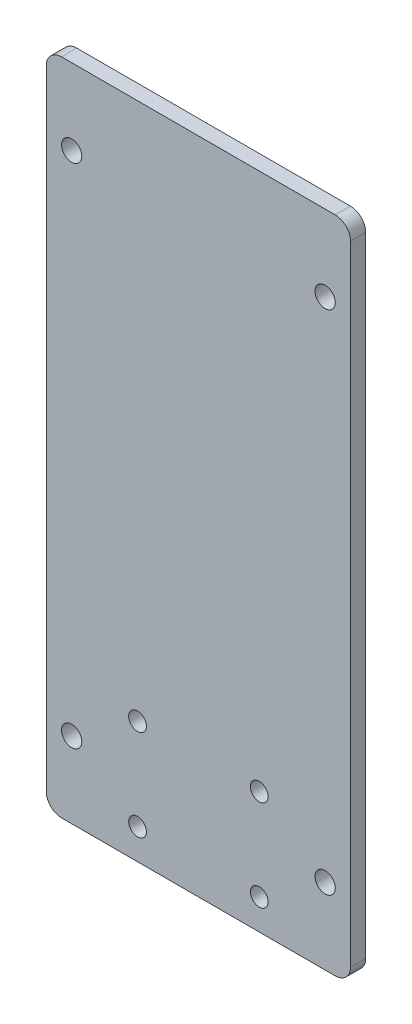
SolidWorks part; units mm, degrees
ref_plane "Płaszczyzna przednia" through (0, 0, 0) normal (0, 0, 1) x (1, 0, 0)
ref_plane "Płaszczyzna górna" through (0, 0, 0) normal (0, 1, 0) x (1, 0, 0)
ref_plane "Płaszczyzna prawa" through (0, 0, 0) normal (1, 0, 0) x (0, 0, -1)
sketch "Szkic1" plane through (0, 0, 0) normal (0, 0, 1) x (1, 0, 0)
  line L1 (0, 0) -> (60, 0)
  line L2 (0, 0) -> (0, 130)
  line L3 (0, 130) -> (60, 130)
  line L4 (60, 0) -> (60, 130)
extrude "Dodanie-wyciągnięcie1" add sketch "Szkic1" along normal blind 3
sketch "Szkic2" plane through (0, 0, 3) normal (0, 0, 1) x (1, 0, 0)
  circle A0 centre (5, 115) radius 2
  circle A1 centre (55, 115) radius 2
  circle A2 centre (5, 15) radius 2
  circle A3 centre (55, 15) radius 2
extrude "Wytnij-wyciągnięcie1" cut sketch "Szkic2" against normal up to next
fillet "Zaokrąglenie1" radius 3 4 edges at (60, 0, 1.5) (0, 0, 1.5) (60, 130, 1.5) (0, 130, 1.5)
sketch "Szkic3" plane through (0, 0, 3) normal (0, 0, 1) x (1, 0, 0)
  circle A0 centre (18, 24) radius 1.75
  circle A1 centre (42, 24) radius 1.75
  circle A2 centre (42, 6) radius 1.75
  circle A3 centre (18, 6) radius 1.75
extrude "Wytnij-wyciągnięcie2" cut sketch "Szkic3" against normal blind 3
